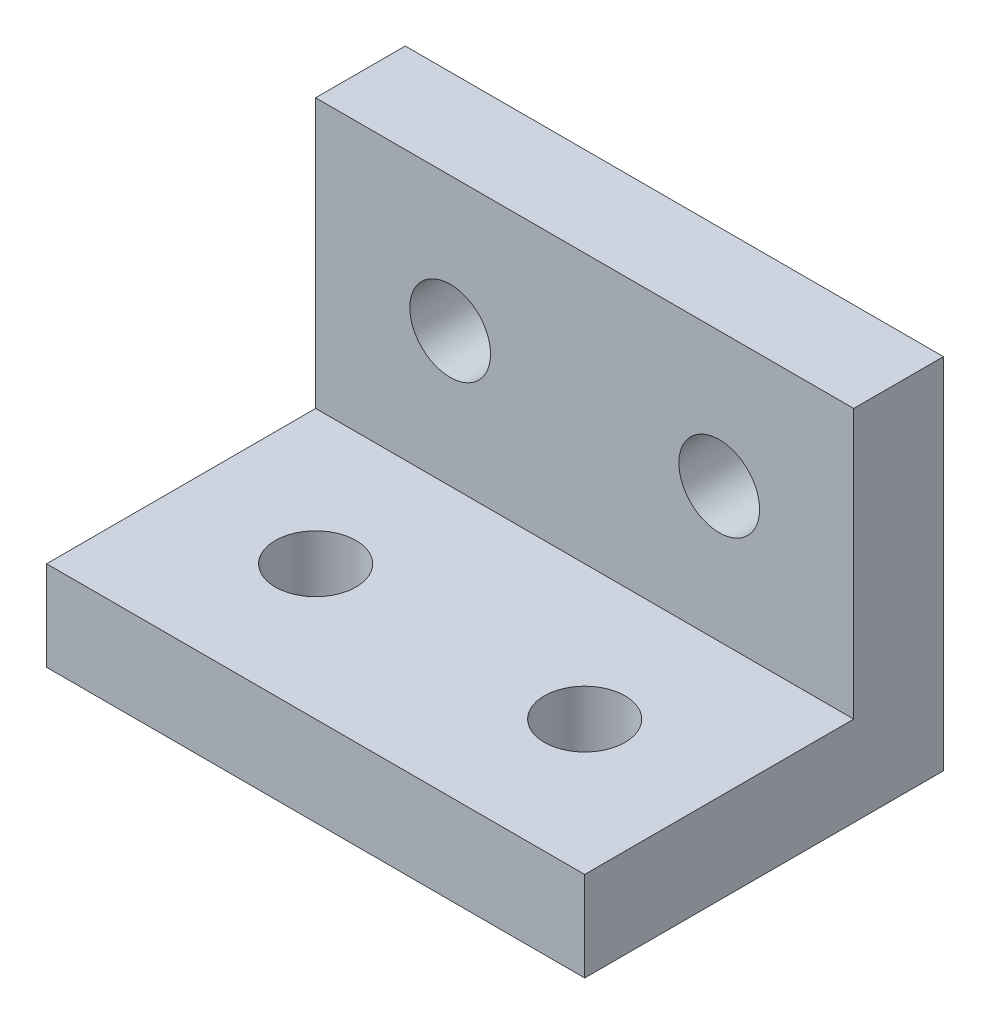
SolidWorks part; units mm, degrees
ref_plane "Front Plane" through (0, 0, 0) normal (0, 0, 1) x (1, 0, 0)
ref_plane "Top Plane" through (0, 0, 0) normal (0, 1, 0) x (1, 0, 0)
ref_plane "Right Plane" through (0, 0, 0) normal (1, 0, 0) x (0, 0, -1)
sketch "Sketch1" plane through (0, 0, 0) normal (1, 0, 0) x (0, 0, -1)
  line L0 (0, 0) -> (0, 20)
  line L1 (0, 0) -> (-20, 0)
  line L2 (-20, 0) -> (-20, 5)
  line L3 (-20, 5) -> (-5, 5)
  line L4 (-5, 5) -> (-5, 20)
  line L5 (-5, 20) -> (0, 20)
  dimension "D1" = 20
  dimension "D2" = 20
  dimension "D3" = 5
  dimension "D4" = 5
extrude "Boss-Extrude1" add sketch "Sketch1" along normal blind 30
sketch "Sketch2" plane through (0, 0, 5) normal (0, 0, 1) x (1, 0, 0)
  line L0 (0, 12.5) -> (14.9508, 12.5) construction
  line L1 (0, 20) -> (0, 5) construction
  circle A0 centre (7.5, 12.5) radius 2.25
  circle A1 centre (22.5, 12.5) radius 2.25
  dimension "D1" = 4.5
  dimension "D2" = 15
  dimension "D3" = 7.5
extrude "Cut-Extrude1" cut sketch "Sketch2" against normal through all
sketch "Sketch3" plane through (0, 5, 0) normal (0, 1, 0) x (1, 0, 0)
  line L0 (0, -12.5) -> (14.7227, -12.5) construction
  line L1 (0, -5) -> (0, -20) construction
  line L2 (30, -5) -> (30, -20) construction
  circle A0 centre (7.5, -12.5) radius 2.25
  circle A1 centre (22.5, -12.5) radius 2.25
  dimension "D1" = 4.5
  dimension "D2" = 15
  dimension "D3" = 7.5
extrude "Cut-Extrude2" cut sketch "Sketch3" against normal through all
chamfer "Chamfer1" [suppressed] distance 10 angle 45
